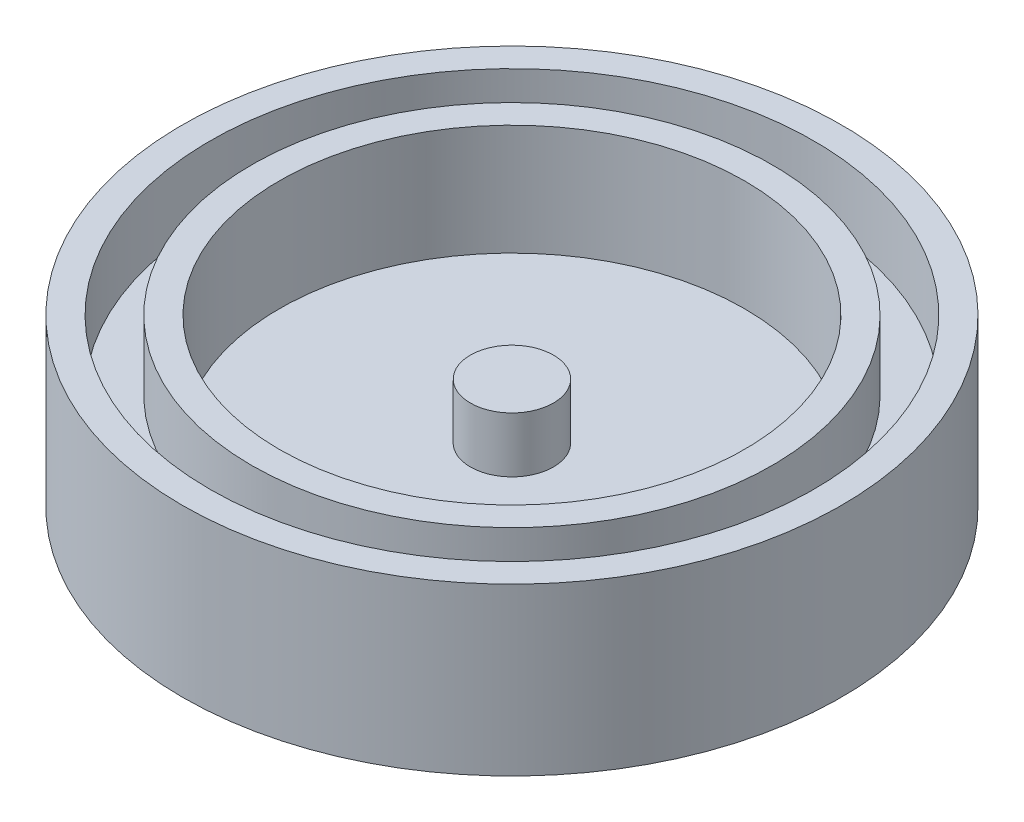
SolidWorks part; units mm, degrees
ref_plane "Front Plane" through (0, 0, 0) normal (0, 0, 1) x (1, 0, 0)
ref_plane "Top Plane" through (0, 0, 0) normal (0, 1, 0) x (1, 0, 0)
ref_plane "Right Plane" through (0, 0, 0) normal (1, 0, 0) x (0, 0, -1)
sketch "Sketch1" plane through (0, 0, 0) normal (0, 0, 1) x (1, 0, 0)
  line L0 (0, 0) -> (-23.8, 0)
  line L1 (-23.8, 0) -> (-23.8, 12)
  line L2 (-23.8, 12) -> (-21.8, 12)
  line L3 (-21.8, 12) -> (-21.8, 7)
  line L4 (-21.8, 7) -> (-18.8, 7)
  line L5 (-18.8, 7) -> (-18.8, 12)
  line L6 (-18.8, 12) -> (-16.8, 12)
  line L7 (-16.8, 12) -> (-16.8, 4)
  line L8 (-16.8, 4) -> (-3, 4)
  line L9 (-3, 4) -> (-3, 8)
  line L10 (-3, 8) -> (0, 8)
  line L11 (0, 8) -> (0, 0)
  dimension "D1" = 16.8
  dimension "D2" = 8
  dimension "D4" = 3
  dimension "D5" = 4
  dimension "D6" = 4
  dimension "D7" = 2
  dimension "D8" = 2
  dimension "D9" = 3
  dimension "D10" = 5
revolve "Revolve1" add sketch "Sketch1" angle 360 about L11
